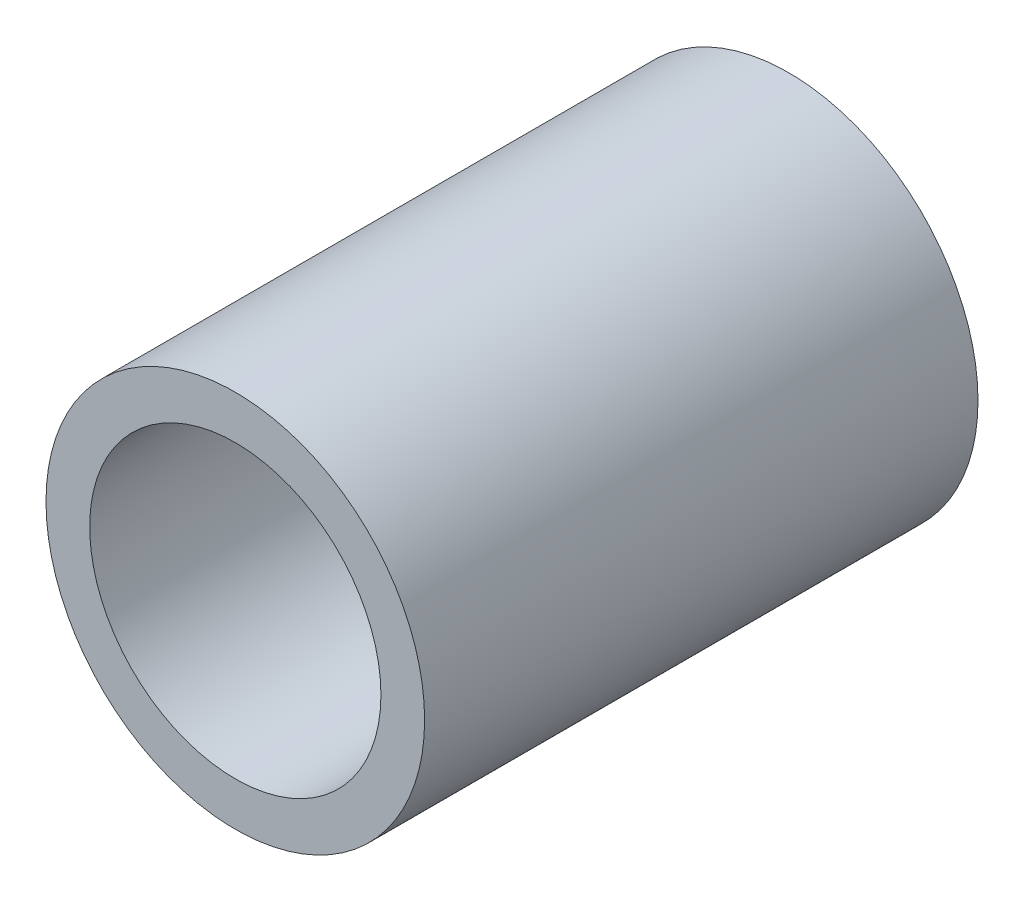
SolidWorks part; units mm, degrees
ref_plane "Front Plane" through (0, 0, 0) normal (0, 0, 1) x (1, 0, 0)
ref_plane "Top Plane" through (0, 0, 0) normal (0, 1, 0) x (1, 0, 0)
ref_plane "Right Plane" through (0, 0, 0) normal (1, 0, 0) x (0, 0, -1)
sketch "Sketch2" plane through (0, 0, 0) normal (0, 0, 1) x (1, 0, 0)
  circle A0 centre (0, 0) radius 3.25
  circle A1 centre (0, 0) radius 2.5
  dimension "D1" = 6.5
  dimension "D2" = 5
extrude "Boss-Extrude1" add sketch "Sketch2" along normal blind 9.5
